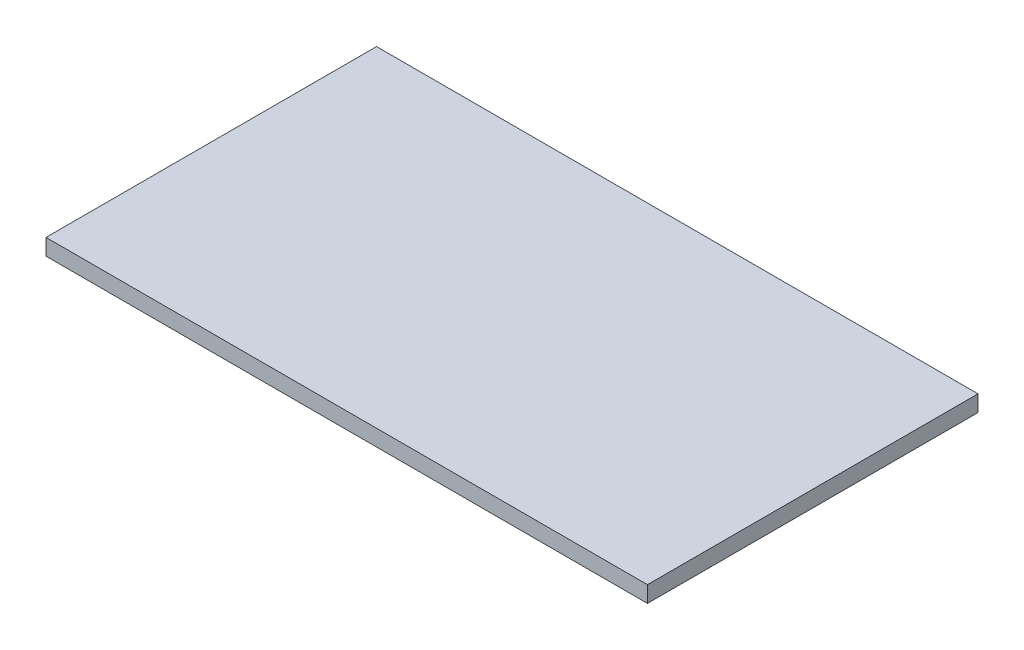
SolidWorks part; units mm, degrees
ref_plane "Front Plane" through (0, 0, 0) normal (0, 0, 1) x (1, 0, 0)
ref_plane "Top Plane" through (0, 0, 0) normal (0, 1, 0) x (1, 0, 0)
ref_plane "Right Plane" through (0, 0, 0) normal (1, 0, 0) x (0, 0, -1)
sketch "Sketch1" plane through (0, 0, 0) normal (0, 1, 0) x (1, 0, 0)
  line L1 (-50.3613, 28.5059) -> (60.6387, 28.5059)
  line L2 (-50.3613, 28.5059) -> (-50.3613, -32.4941)
  line L3 (-50.3613, -32.4941) -> (60.6387, -32.4941)
  line L4 (60.6387, 28.5059) -> (60.6387, -32.4941)
extrude "Boss-Extrude1" add sketch "Sketch1" along normal blind 3
